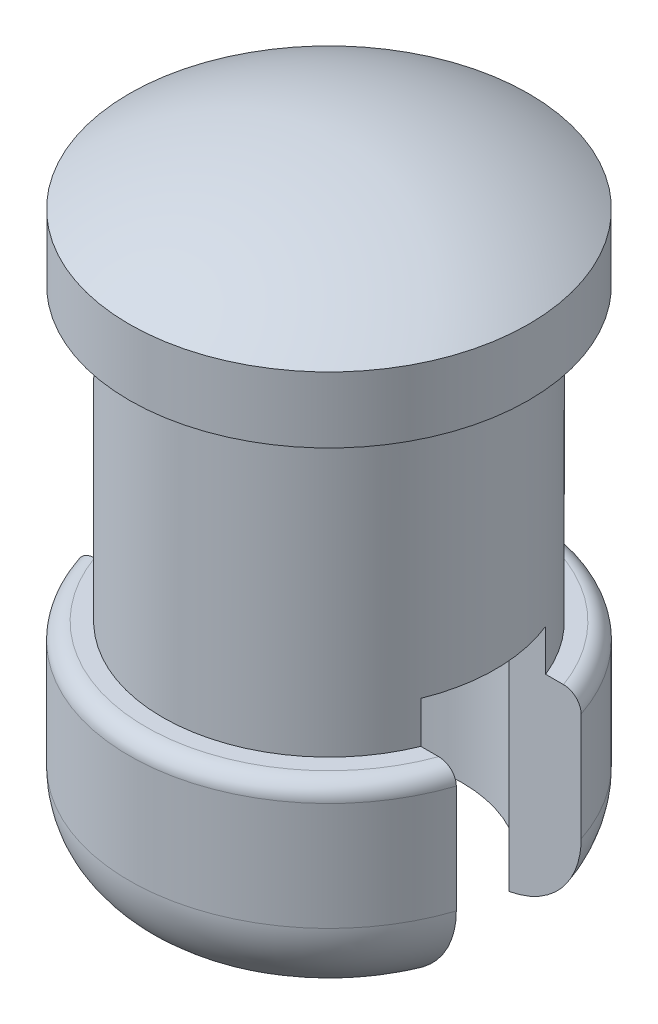
SolidWorks part; units mm, degrees
ref_plane "前视基准面" through (0, 0, 0) normal (0, 0, 1) x (1, 0, 0)
ref_plane "上视基准面" through (0, 0, 0) normal (0, 1, 0) x (1, 0, 0)
ref_plane "右视基准面" through (0, 0, 0) normal (1, 0, 0) x (0, 0, -1)
sketch "草图3" plane through (0, 0, 0) normal (1, 0, 0) x (0, 0, -1)
  line L0 (0, 28.2119) -> (0, -26.3712) construction
  line L1 (2.4, 6.7914) -> (2.4, 6)
  line L2 (2.4, 6) -> (2, 6)
  line L3 (2, 6) -> (2, 2.5)
  line L4 (2, 2.5) -> (2.2, 2.5)
  line L5 (0, 0) -> (1.4, 0)
  line L6 (2.4, 1) -> (2.4, 2.3)
  line L7 (0, 7.5) -> (0, 0)
  arc A0 (0, 7.5) -> (2.4, 6.7914) centre (0, 3.0813) cw
  arc A1 (2.4, 2.3) -> (2.2, 2.5) centre (2.2, 2.3) ccw
  arc A2 (1.4, 0) -> (2.4, 1) centre (1.4, 1) ccw
  dimension "D6" = 0.2
  dimension "D7" = 1
  dimension "D1" = 7.5
  dimension "D2" = 1.5
  dimension "D3" = 2.4
  dimension "D4" = 3.5
  dimension "D5" = 2
revolve "旋转1" add sketch "草图3" angle 360 about L0
sketch "草图4" plane through (0, 0, 0) normal (0, -1, 0) x (1, 0, 0)
  circle A0 centre (0, 0) radius 1.6
  dimension "D1" = 3.2
extrude "切除-拉伸1" cut sketch "草图4" against normal blind 6
sketch "草图5" plane through (0, 0, 0) normal (0, 1, 0) x (1, 0, 0)
  line L0 (-3.9021, 0) -> (4.5084, 0) construction
  line L1 (-3.3544, -0.75) -> (3.4914, -0.75)
  line L2 (-3.3544, -0.75) -> (-3.3544, 0.75)
  line L3 (-3.3544, 0.75) -> (3.4914, 0.75)
  line L4 (3.4914, -0.75) -> (3.4914, 0.75)
  dimension "D1" = 1.5
extrude "切除-拉伸3" cut sketch "草图5" along normal blind 3
